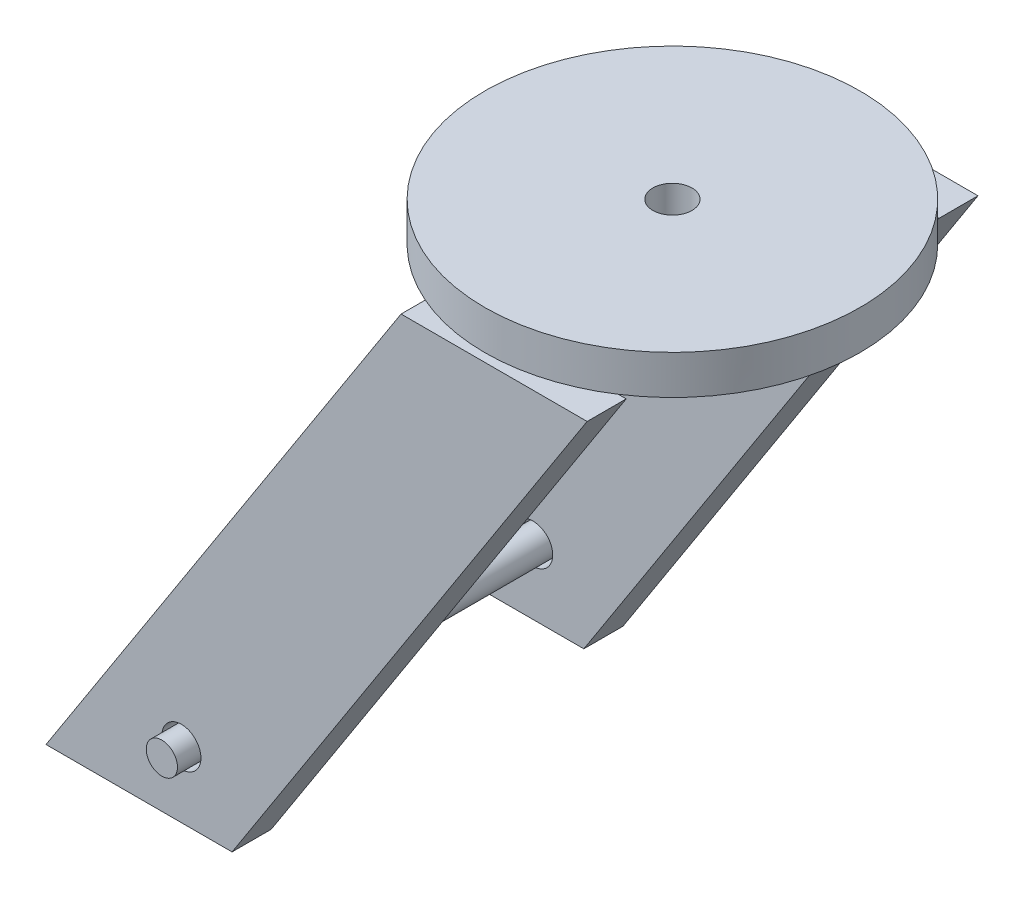
SolidWorks part; units mm, degrees
material "Stainless Steel (ferritic)"
ref_plane "Front Plane" through (0, 0, 0) normal (0, 0, 1) x (1, 0, 0)
ref_plane "Top Plane" through (0, 0, 0) normal (0, 1, 0) x (1, 0, 0)
ref_plane "Right Plane" through (0, 0, 0) normal (1, 0, 0) x (0, 0, -1)
sketch "Sketch1" plane through (0, 0, 0) normal (0, 0, 1) x (1, 0, 0)
  line L0 (0, 0) -> (90.8425, 140.8059)
  line L1 (90.8425, 140.8059) -> (138.4448, 140.8059)
  line L2 (138.4448, 140.8059) -> (47.6022, 0)
  line L3 (47.6022, 0) -> (0, 0)
  line L4 (23.8011, 0) -> (114.6437, 140.8059) construction
  line L5 (34.6437, 14.2699) -> (34.6437, 136.3766) construction
  circle A0 centre (34.6437, 16.8059) radius 5
  circle A1 centre (34.6437, 16.8059) radius 100 construction
  point P11 (34.6437, -83.1941)
  dimension "D1" = 10
  dimension "D5" = 200
  dimension "D2" = 20
  dimension "D3" = 40
  dimension "D4" = 80
  dimension "D6" = 224
extrude "Boss-Extrude1" add sketch "Sketch1" along normal blind 10 from offset 40
ref_plane "Plane1" through (0, 0, 0) normal (0, 0, 1) x (1, 0, 0)
mirror "Mirror2" about plane through (0, 0, 0) normal (0, 0, 1) of bodies 101
sketch "Sketch2" plane through (0, 140.8059, 0) normal (0, 1, 0) x (1, 0, 0)
  line L0 (90.8425, 50) -> (129.5069, -50) construction
  line L1 (138.4448, -50) -> (90.8425, -50) construction
  circle A1 centre (110.1184, 0.1457) radius 5
  circle A2 centre (110.1184, 0.1457) radius 48
  dimension "D1" = 10
  dimension "D2" = 43
extrude "Boss-Extrude2" add sketch "Sketch2" along normal blind 10
sketch "Sketch3" plane through (0, 0, 50) normal (0, 0, 1) x (1, 0, 0)
  circle A0 centre (34.6437, 16.8059) radius 5 construction
  circle A1 centre (34.6437, 16.8059) radius 4
  dimension "D1" = 1
extrude "Boss-Extrude3" add sketch "Sketch3" along normal blind 5 and the other way blind 105 separate body
